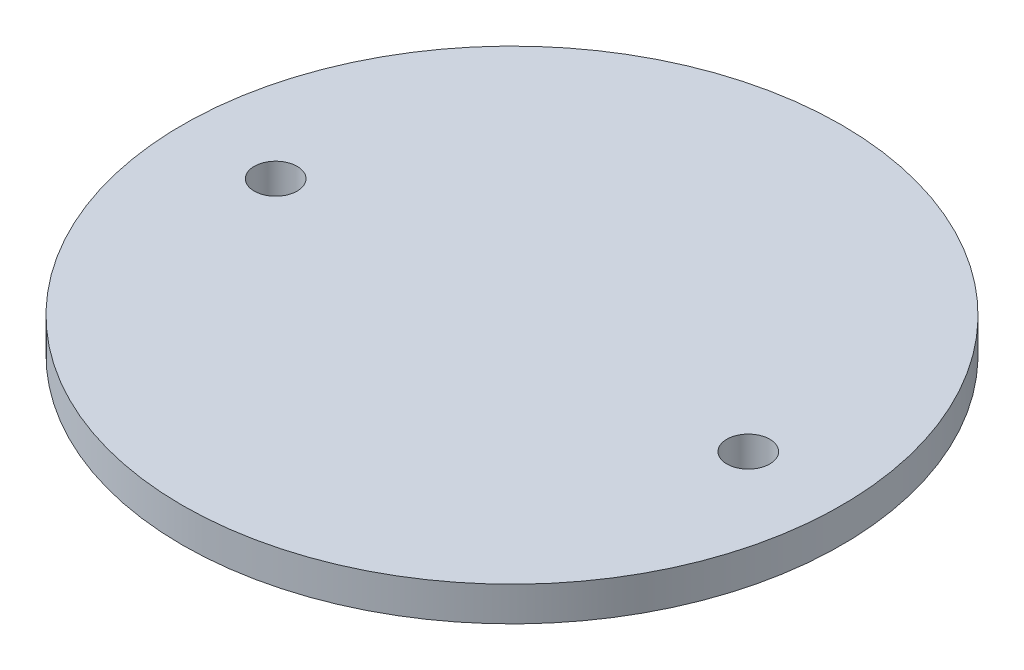
SolidWorks part; units mm, degrees
material "Balsa"
ref_plane "Front Plane" through (0, 0, 0) normal (0, 0, 1) x (1, 0, 0)
ref_plane "Top Plane" through (0, 0, 0) normal (0, 1, 0) x (1, 0, 0)
ref_plane "Right Plane" through (0, 0, 0) normal (1, 0, 0) x (0, 0, -1)
sketch "Sketch1" plane through (0, 0, 0) normal (0, 1, 0) x (1, 0, 0)
  line L0 (-38.35, 0) -> (38.35, 0) construction
  line L1 (0, 38.35) -> (0, -38.35) construction
  circle A0 centre (0, 0) radius 38.35
  circle A1 centre (-27.5, 0) radius 2.5
  circle A2 centre (27.5, 0) radius 2.5
  dimension "D1" = 55
  dimension "D2" = 76.7
  dimension "D3" = 5
extrude "Boss-Extrude1" add sketch "Sketch1" along normal blind 4
